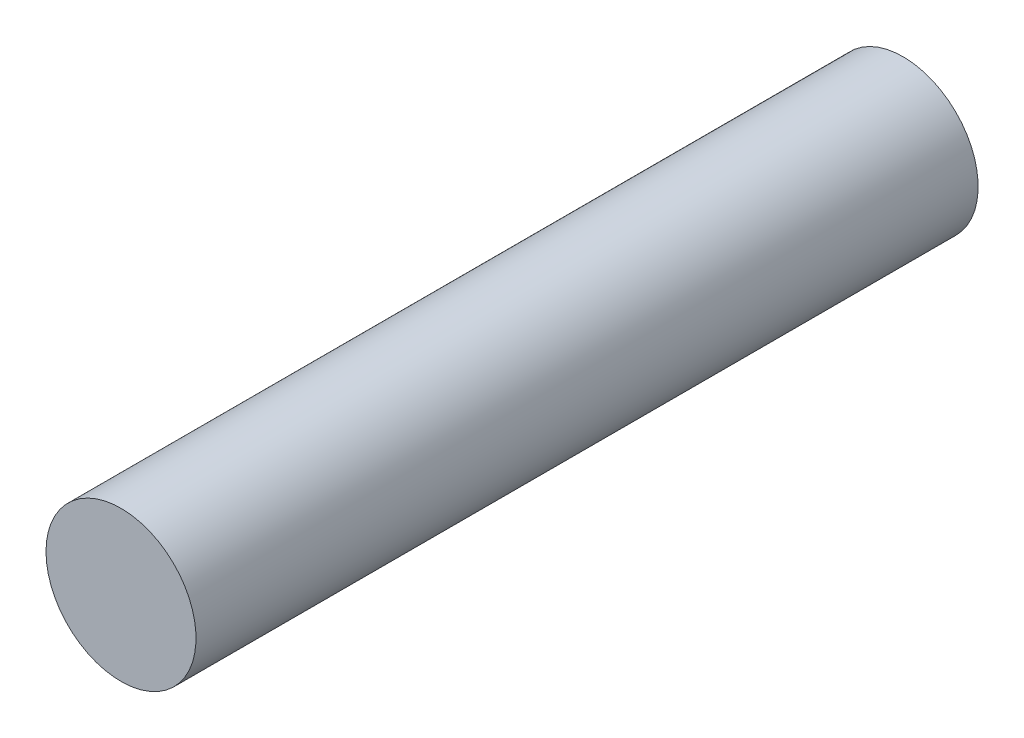
SolidWorks part; units mm, degrees
ref_plane "Front Plane" through (0, 0, 0) normal (0, 0, 1) x (1, 0, 0)
ref_plane "Top Plane" through (0, 0, 0) normal (0, 1, 0) x (1, 0, 0)
ref_plane "Right Plane" through (0, 0, 0) normal (1, 0, 0) x (0, 0, -1)
sketch "Sketch1" plane through (0, 0, 0) normal (0, 0, 1) x (1, 0, 0)
  circle A0 centre (0, 0) radius 35
  dimension "D1" = 70
extrude "Boss-Extrude1" add sketch "Sketch1" along normal blind 365
